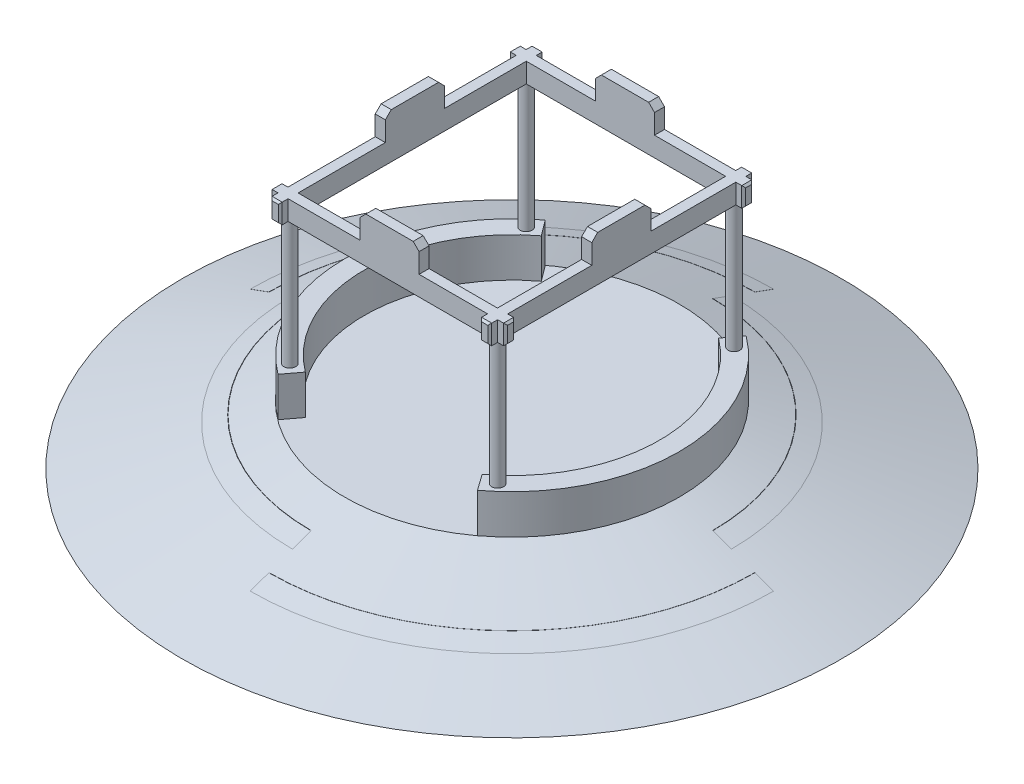
SolidWorks part; units mm, degrees
material "ABS PC"
ref_plane "Front" through (0, 0, 0) normal (0, 0, 1) x (1, 0, 0)
ref_plane "Top" through (0, 0, 0) normal (0, 1, 0) x (1, 0, 0)
ref_plane "Right" through (0, 0, 0) normal (1, 0, 0) x (0, 0, -1)
sketch "草图1" plane through (0, 0, 0) normal (0, 1, 0) x (1, 0, 0)
  line L9 (-450, -599.5126) -> (450, -599.5126)
  line L10 (-450, -599.5126) -> (-450, 599.5126)
  line L11 (-450, 599.5126) -> (450, 599.5126)
  line L12 (450, -599.5126) -> (450, 599.5126)
  line L13 (-450, -599.5126) -> (450, 599.5126) construction
  line L14 (-450, 599.5126) -> (450, -599.5126) construction
  circle A0 centre (0, 0) radius 850
  circle A1 centre (0, 0) radius 850
  circle A2 centre (0, 0) radius 749.6101
sketch "草图2" plane through (0, 0, 0) normal (0, 0, 1) x (1, 0, 0)
  line L0 (850, 0) -> (850, -300)
  line L1 (850, 0) -> (-850, 0) construction
  line L2 (0, 0) -> (0, -300)
  line L3 (0, 0) -> (850, 0)
  line L4 (0, -300) -> (850, -300)
  line L5 (850, -300) -> (1674.2432, -300)
  line L6 (1674.2432, -300) -> (850, 0)
revolve "旋转1" add sketch "草图2" angle 360 about L2
sketch "草图7" plane through (0, 0, 0) normal (0, 1, 0) x (1, 0, 0)
  line L0 (-450.2097, -599.3552) -> (-510, -678.4448)
  line L1 (-509.6677, 678.6944) -> (-450, 599.5126)
  line L2 (510.0573, 679.957) -> (450, 599.5126)
  line L3 (448.935, -600.3105) -> (507.1696, -682.1136)
  arc A0 (-450, 599.5126) -> (-450.2097, -599.3552) centre (0, 0) ccw
  arc A1 (450, 599.5126) -> (448.935, -600.3105) centre (0, 0) cw
  arc A2 (-509.6677, 678.6944) -> (-510, -678.4448) centre (0, 0) ccw
  arc A3 (510.0573, 679.957) -> (507.1696, -682.1136) centre (0, 0) cw
extrude "凸台-拉伸1" add sketch "草图7" along normal blind 200
sketch "草图9" plane through (0, 200, 0) normal (0, 1, 0) x (1, 0, 0)
  circle A0 centre (-527.922, -600.3944) radius 30
  circle A1 centre (527.922, -600.3944) radius 30
  circle A2 centre (527.922, 600.3944) radius 30
  circle A3 centre (-527.922, 600.3944) radius 30
  point P0 (0, 0)
extrude "凸台-拉伸2" add sketch "草图9" along normal blind 650 separate body
sketch "草图10" plane through (0, 850, 0) normal (0, 1, 0) x (1, 0, 0)
  line L0 (-506.5041, -630.3944) -> (-506.5041, -670.3944)
  line L1 (-506.5041, -579.7431) -> (506.3278, -579.7431)
  line L2 (-506.5041, -579.7431) -> (-506.5041, 579.5692)
  line L3 (-506.5041, 579.5692) -> (506.3278, 579.5692)
  line L4 (506.3278, -579.7431) -> (506.3278, 579.5692)
  line L5 (-557.922, -630.3944) -> (-557.922, -670.3944)
  line L6 (-557.922, -670.3944) -> (-506.5041, -670.3944)
  line L7 (-557.922, -579.7431) -> (-597.922, -579.7431)
  line L8 (-557.922, -630.3944) -> (557.922, -630.3944)
  line L9 (-557.922, -630.3944) -> (-557.922, 630.3944)
  line L10 (-557.922, 630.3944) -> (557.922, 630.3944)
  line L11 (557.922, -630.3944) -> (557.922, 630.3944)
  line L12 (-597.922, -579.7431) -> (-597.922, -630.3944)
  line L13 (-557.922, -630.3944) -> (-597.922, -630.3944)
  line L14 (506.3278, -630.3944) -> (506.3278, -670.3944)
  line L15 (557.922, -630.3944) -> (557.922, -670.3944)
  line L16 (557.922, -670.3944) -> (506.3278, -670.3944)
  line L17 (557.922, -579.7431) -> (597.922, -579.7431)
  line L18 (597.922, -579.7431) -> (597.922, -630.3944)
  line L19 (597.922, -630.3944) -> (557.922, -630.3944)
  line L20 (506.3278, 630.3944) -> (506.3278, 670.3944)
  line L21 (506.3278, 670.3944) -> (557.922, 670.3944)
  line L22 (557.922, 670.3944) -> (557.922, 630.3944)
  line L23 (557.922, 630.3944) -> (597.922, 630.3944)
  line L24 (597.922, 630.3944) -> (597.922, 579.5692)
  line L25 (597.922, 579.5692) -> (557.922, 579.5692)
  line L26 (-506.5041, 630.3944) -> (-506.5041, 670.3944)
  line L27 (-506.5041, 670.3944) -> (-557.922, 670.3944)
  line L28 (-557.922, 670.3944) -> (-557.922, 630.3944)
  line L29 (-557.922, 630.3944) -> (-597.922, 630.3944)
  line L30 (-597.922, 630.3944) -> (-597.922, 579.5692)
  line L31 (-597.922, 579.5692) -> (-557.922, 579.5692)
  line L32 (-557.922, -579.7431) -> (-506.5041, -579.7431)
  line L33 (-506.5041, -579.7431) -> (-506.5041, -630.3944)
  line L34 (506.3278, -579.7431) -> (506.3278, -633.089)
  line L35 (506.3278, -579.7431) -> (557.922, -579.7431)
  line L36 (506.3278, 630.3944) -> (506.3278, 579.5692)
  line L37 (506.3278, 579.5692) -> (557.922, 579.5692)
  line L38 (-557.922, 579.5692) -> (-506.5041, 579.5692)
  line L39 (-506.5041, 630.3944) -> (-506.5041, 579.5692)
  circle A0 centre (527.922, 600.3944) radius 30 construction
  point P0 (0, 0)
  circle M1 centre (-527.922, 600.3944) radius 30
extrude "凸台-拉伸3" add sketch "草图10" along normal blind 100 contours L30 L31 L9 L29 | L10 L9 M1 | L9 L38 M1 | L39 L38 M1 | L39 L10 M1 | L27 L28 L10 L26 | L39 L3 M1 | L38 L2 M1 | L38 L9 L32 L2 M1 | L10 L39 L3 L36 M1 | L13 L9 L7 L12 | L33 L32 L9 L8 | L8 L5 L6 L0 | L34 L1 L33 L8 | L35 L34 L8 L11 | L16 L15 L8 L14 | L19 L18 L17 L11 | L22 L21 L20 L10 | L36 L37 L11 L10 | L25 L24 L23 L11
sketch "草图11" plane through (0, 850, 0) normal (0, 1, 0) x (1, 0, 0)
  line L0 (506.1614, -579.7431) -> (506.1614, 579.5692)
  line L1 (506.3278, 579.5692) -> (549.5161, 579.5692) construction
  line L2 (-506.5041, 579.5692) -> (597.922, 579.5692) construction
  line L3 (557.8968, 579.5692) -> (557.8968, -579.7431)
  line L4 (-506.5041, -579.7431) -> (597.922, -579.7431) construction
  line L5 (506.1614, -579.7431) -> (557.8968, -579.7431)
  line L6 (506.1614, 579.5692) -> (557.8968, 579.5692)
extrude "凸台-拉伸4" add sketch "草图11" along normal blind 100
chamfer "倒角1" distance 10 4 edges at (597.922, 900, 630.3944) (597.922, 850, 605.0687) (597.922, 950, 605.0687) (597.922, 900, 579.7431)
chamfer "倒角2" distance 10 angle 45 4 edges at (506.3278, 900, 670.3944) (532.1249, 850, 670.3944) (532.1249, 950, 670.3944) (557.922, 900, 670.3944)
chamfer "倒角3" distance 10 angle 45 24 edges at (597.922, 900, -579.5692) (597.922, 850, -604.9818) (597.922, 950, -604.9818) (597.922, 900, -630.3944) (-506.5041, 900, -670.3944) (-532.213, 850, -670.3944) (-532.213, 950, -670.3944) (-557.922, 900, -670.3944) (557.922, 900, -670.3944) (532.1249, 850, -670.3944) (532.1249, 950, -670.3944) (506.3278, 900, -670.3944) (-597.922, 900, -630.3944) (-597.922, 850, -604.9818) (-597.922, 950, -604.9818) (-597.922, 900, -579.5692) (-597.922, 900, 579.7431) (-597.922, 850, 605.0687) (-597.922, 950, 605.0687) (-597.922, 900, 630.3944) (-557.922, 900, 670.3944) (-532.213, 850, 670.3944) (-532.213, 950, 670.3944) (-506.5041, 900, 670.3944)
sketch "草图14" plane through (0, 950, 0) normal (0, 1, 0) x (1, 0, 0)
  line L0 (506.1614, 579.5692) -> (506.1614, -579.7431) construction
  line L1 (557.8968, -152.1092) -> (506.1614, -152.1092)
  line L2 (557.8968, -152.1092) -> (557.8968, 147.8908)
  line L3 (557.8968, 147.8908) -> (506.1614, 147.8908)
  line L4 (506.1614, -152.1092) -> (506.1614, 147.8908)
  line L5 (557.8968, -152.1092) -> (506.1614, 147.8908) construction
  line L6 (557.8968, 147.8908) -> (506.1614, -152.1092) construction
  line L7 (557.8968, -579.7431) -> (557.8968, 579.5692) construction
  line L12 (-506.5041, -579.7431) -> (506.1614, -579.7431) construction
  line L13 (-141.5801, -630.3944) -> (158.8405, -630.3944)
  line L14 (-141.5801, -630.3944) -> (-141.5801, -579.7431)
  line L15 (-141.5801, -579.7431) -> (158.8405, -579.7431)
  line L16 (158.8405, -630.3944) -> (158.8405, -579.7431)
  line L17 (-141.5801, -630.3944) -> (158.8405, -579.7431) construction
  line L18 (-141.5801, -579.7431) -> (158.8405, -630.3944) construction
  line L19 (-506.5041, -630.3944) -> (506.3278, -630.3944) construction
  line L20 (-557.922, -579.7431) -> (-557.922, 579.5692) construction
  line L21 (-506.5041, -136.327) -> (-557.922, -136.327)
  line L22 (-506.5041, -136.327) -> (-506.5041, 163.673)
  line L23 (-506.5041, 163.673) -> (-557.922, 163.673)
  line L24 (-557.922, -136.327) -> (-557.922, 163.673)
  line L25 (-506.5041, -136.327) -> (-557.922, 163.673) construction
  line L26 (-506.5041, 163.673) -> (-557.922, -136.327) construction
  line L27 (-506.5041, -579.7431) -> (-506.5041, 579.5692) construction
  line L28 (-506.5041, 630.3944) -> (506.3278, 630.3944) construction
  line L29 (-155.0579, 579.5692) -> (144.9421, 579.5692)
  line L30 (-155.0579, 579.5692) -> (-155.0579, 630.3944)
  line L31 (-155.0579, 630.3944) -> (144.9421, 630.3944)
  line L32 (144.9421, 579.5692) -> (144.9421, 630.3944)
  line L33 (-155.0579, 579.5692) -> (144.9421, 630.3944) construction
  line L34 (-155.0579, 630.3944) -> (144.9421, 579.5692) construction
  line L35 (-506.5041, 579.5692) -> (506.1614, 579.5692) construction
  point P0 (532.0291, -2.1092)
  point P12 (8.6302, -605.0687)
  point P21 (-532.213, 13.673)
  point P30 (-5.0579, 604.9818)
  line M5 (-506.5041, 579.5692) -> (506.1614, 579.5692)
  line M6 (506.1614, 579.5692) -> (506.1614, -579.7431)
  line M7 (506.1614, -579.7431) -> (-506.5041, -579.7431)
  line M8 (-506.5041, -579.7431) -> (-506.5041, 579.5692)
  line M15 (506.3278, 630.3944) -> (-506.5041, 630.3944)
  line M22 (-557.922, 579.5692) -> (-557.922, -579.7431)
  line M29 (-506.5041, -630.3944) -> (506.3278, -630.3944)
  line M36 (557.8968, -579.7431) -> (557.8968, 579.5692)
extrude "凸台-拉伸5" add sketch "草图14" along normal blind 130 contours L16 L14 M29 M7 | L3 L1 M36 M6 | L32 L30 M5 M15 | L23 L21 M8 M22
chamfer "倒角6" distance 30 angle 45 1 edges at (532.0291, 1080, 152.1092)
chamfer "倒角7" distance 30 angle 45 7 edges at (532.0291, 1080, -147.8908) (144.9421, 1080, -604.9818) (-155.0579, 1080, -604.9818) (-532.213, 1080, -163.673) (-532.213, 1080, 136.327) (-141.5801, 1080, 605.0687) (158.8405, 1080, 605.0687)
sketch "草图16" plane through (0, 0, 0) normal (0, 0, 1) x (1, 0, 0)
  line L0 (0, 0) -> (0, -174)
  line L1 (0, -174) -> (1329, -174)
  line L2 (1329, -174) -> (1235.0307, -139.798)
  line L3 (1235.0307, -139.798) -> (0, -139.798)
  line L4 (0, -140.5117) -> (0, -174)
  line L5 (0, -139.798) -> (0, -174)
revolve "旋转3" add sketch "草图16" angle 90 about L0
sketch "草图19" plane through (0, 0, 0) normal (0, 0, 1) x (1, 0, 0)
  line L0 (0, 0) -> (0, -174)
  line L1 (0, -174) -> (-1329, -174)
  line L2 (-1329, -174) -> (-1235.0307, -139.798)
  line L3 (-1235.0307, -139.798) -> (0, -139.798)
  line L4 (0, -139.798) -> (0, -174)
revolve "旋转4" add sketch "草图19" angle 90 about L0
sketch "草图20" plane through (0, 0, 0) normal (0, 0, 1) x (1, 0, 0)
  line L0 (0, 0) -> (0, -96)
  line L1 (0, -96) -> (1115, -96)
  line L2 (1115, -96) -> (1021.0307, -61.798)
  line L3 (1021.0307, -61.798) -> (0, -61.798)
  line L4 (0, -61.798) -> (0, -96)
revolve "旋转5" add sketch "草图20" angle 90 about L0
sketch "草图21" plane through (0, 0, 0) normal (0, 0, 1) x (1, 0, 0)
  line L0 (0, 0) -> (0, -96)
  line L1 (0, -96) -> (0, -61.798) construction
  line L2 (0, -96) -> (0, -61.798) construction
  line L3 (0, -96) -> (-1115, -96)
  line L4 (-1115, -96) -> (-1021.0307, -61.798)
  line L5 (-1021.0307, -61.798) -> (0, -61.798)
  line L6 (0, -61.798) -> (0, -96)
revolve "旋转6" add sketch "草图21" angle 90 about L0
